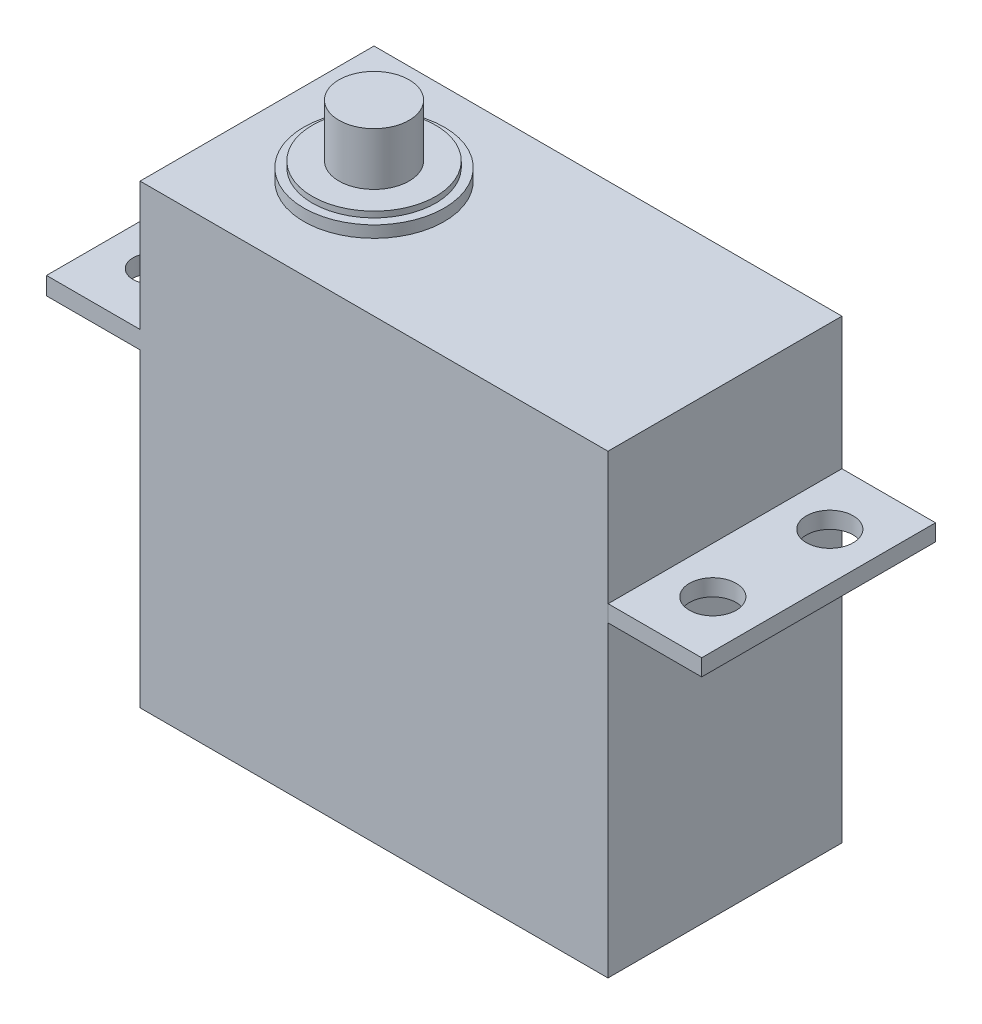
SolidWorks part; units mm, degrees
other "标注1"
sketch "草图8" plane through (-28, 25.5, 20) normal (-0.0252, 0.8568, 0.515) x (0.9994, 0.009, 0.0338)
ref_plane "前视基准面" through (0, 0, 0) normal (0, 0, 1) x (1, 0, 0)
ref_plane "上视基准面" through (0, 0, 0) normal (0, 1, 0) x (1, 0, 0)
ref_plane "右视基准面" through (0, 0, 0) normal (1, 0, 0) x (0, 0, -1)
other "Configuration Table"
sketch "草图1" plane through (0, 0, 0) normal (0, 0, 1) x (1, 0, 0)
  line L1 (-20, 19.5) -> (20, 19.5)
  line L2 (-20, 19.5) -> (-20, -19.5)
  line L3 (-20, -19.5) -> (20, -19.5)
  line L4 (20, 19.5) -> (20, -19.5)
  line L5 (-20, 19.5) -> (20, -19.5) construction
  line L6 (-20, -19.5) -> (20, 19.5) construction
  point P0 (0, 0)
extrude "凸台-拉伸1" add sketch "草图1" along normal blind 20
sketch "草图3" plane through (0, 19.5, 0) normal (0, 1, 0) x (1, 0, 0)
  circle A0 centre (-10, -10) radius 6
extrude "凸台-拉伸2" add sketch "草图3" along normal blind 1
sketch "草图4" plane through (0, 0, 0) normal (0, 1, 0) x (1, 0, 0)
  circle A0 centre (-10, -10) radius 3
  point P2 (-33.6211, -11.5509)
extrude "凸台-拉伸4" add sketch "草图4" along normal blind 25.5
sketch "草图5" plane through (-20, 0, 0) normal (-1, 0, 0) x (0, 0, 1)
  line L0 (0, 19.5) -> (0, -19.5) construction
  line L1 (0, 8.5152) -> (20, 8.5152)
  line L2 (0, 8.5152) -> (0, 7)
  line L3 (0, 7) -> (20, 7)
  line L4 (20, 8.5152) -> (20, 7)
  line L5 (20, 19.5) -> (20, -19.5) construction
extrude "凸台-拉伸5" add sketch "草图5" along normal blind 8
sketch "草图6" plane through (20, 0, 0) normal (1, 0, 0) x (0, 0, -1)
  line L1 (0, 8.2039) -> (-19.9885, 8.2039)
  line L2 (0, 8.2039) -> (0, 6.7834)
  line L3 (0, 6.7834) -> (-19.9885, 6.7834)
  line L4 (-19.9885, 8.2039) -> (-19.9885, 6.7834)
extrude "凸台-拉伸8" add sketch "草图6" along normal blind 8
sketch "草图7" plane through (0, 8.5152, 0) normal (0, 1, 0) x (1, 0, 0)
  circle A0 centre (-24, -5) radius 1.7105
  circle A1 centre (-24, -15) radius 1.6046
  circle A2 centre (23.9632, -5) radius 2
  circle A3 centre (23.9632, -15) radius 2
  dimension "D2" = 10
  dimension "D1" = 10
extrude "切除-拉伸2" cut sketch "草图7" against normal blind 3
sketch "草图9" plane through (0, 19.5, 0) normal (0, 1, 0) x (1, 0, 0)
  circle A0 centre (-10, -10) radius 5.2738
extrude "凸台-拉伸9" add sketch "草图9" along normal blind 1.5
